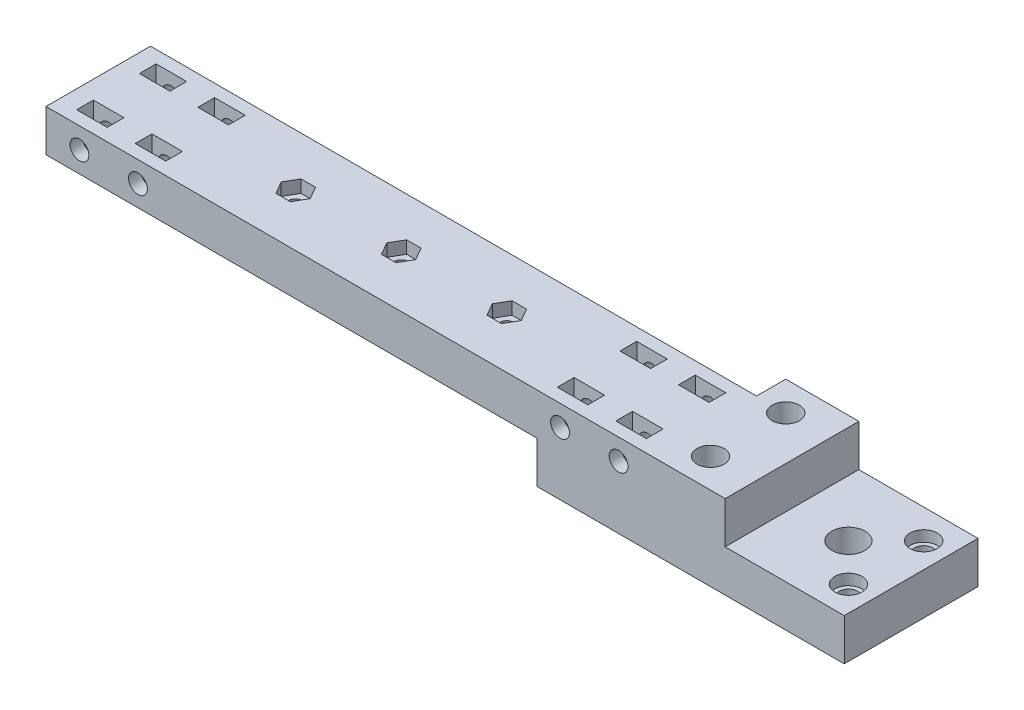
SolidWorks part; units mm, degrees
ref_plane "Front Plane" through (0, 0, 0) normal (0, 0, 1) x (1, 0, 0)
ref_plane "Top Plane" through (0, 0, 0) normal (0, 1, 0) x (1, 0, 0)
ref_plane "Right Plane" through (0, 0, 0) normal (1, 0, 0) x (0, 0, -1)
sketch "Sketch1" plane through (0, 0, 0) normal (0, 1, 0) x (1, 0, 0)
  line L7 (0, 0) -> (145, 0)
  line L8 (0, 0) -> (0, 25)
  line L9 (0, 25) -> (145, 25)
  line L10 (145, 0) -> (145, 25)
  dimension "D1" = 25
  dimension "D3" = 145
extrude "Boss-Extrude1" add sketch "Sketch1" along normal blind 10
sketch "Sketch2" plane through (0, 10, 0) normal (0, 1, 0) x (1, 0, 0)
  line L5 (145, 0) -> (162.5, 0)
  line L6 (145, 0) -> (145, 32)
  line L7 (145, 32) -> (162.5, 32)
  line L8 (162.5, 0) -> (162.5, 32)
  dimension "D1" = 17.5
  dimension "D2" = 32
extrude "Boss-Extrude2" add sketch "Sketch2" against normal blind 10
sketch "Sketch4" plane through (0, 0, 0) normal (0, -1, 0) x (1, 0, 0)
  line L0 (162.5, -32) -> (191, -32) construction
  line L1 (162.5, 0) -> (117.5, 0) construction
  line L2 (0, 0) -> (162.5, 0) construction
  line L4 (117.5, 0) -> (191, 0)
  line L5 (117.5, 0) -> (117.5, -32)
  line L6 (117.5, -32) -> (191, -32)
  line L7 (191, 0) -> (191, -32)
  dimension "D1" = 28.5
  dimension "D2" = 45
extrude "Boss-Extrude3" add sketch "Sketch4" along normal blind 10
sketch "Sketch5" plane through (0, -10, 0) normal (0, -1, 0) x (1, 0, 0)
  line L0 (191, -16) -> (117.5, -16) construction
  line L1 (191, -32) -> (191, 0) construction
  line L2 (117.5, 0) -> (117.5, -32) construction
  line L3 (117.5, -12.5) -> (191, -12.5) construction
  line L4 (117.5, 0) -> (117.5, -25) construction
  circle A0 centre (185, -7) radius 2.25
  circle A1 centre (152, -7) radius 2.25
  circle A2 centre (185, -25) radius 2.25
  circle A3 centre (152, -25) radius 2.25
  dimension "D1" = 4.5
  dimension "D2" = 6
  dimension "D3" = 9
  dimension "D5" = 33
  dimension "D4" = 2
extrude "Cut-Extrude1" cut sketch "Sketch5" against normal up to next
sketch "Sketch6" plane through (0, -10, 0) normal (0, -1, 0) x (1, 0, 0)
  line L0 (191, -16) -> (117.5, -16) construction
  line L1 (191, -32) -> (191, 0) construction
  line L2 (117.5, 0) -> (117.5, -32) construction
  circle A0 centre (152, -7) radius 4.2
  circle A1 centre (185, -7) radius 4.2
  circle A2 centre (185, -25) radius 4.2
  circle A3 centre (152, -25) radius 4.2
  dimension "D1" = 8.4
  dimension "D3" = 33
  dimension "D2" = 2
extrude "Cut-Extrude2" cut sketch "Sketch6" against normal blind 2.4
sketch "Sketch7" plane through (0, -7.6, 0) normal (0, -1, 0) x (1, 0, 0)
  line L0 (191, -16) -> (117.5, -16) construction
  line L1 (191, -32) -> (191, 0) construction
  line L2 (117.5, 0) -> (117.5, -32) construction
  circle A0 centre (152, -7) radius 3.25
  circle A1 centre (185, -7) radius 3.25
  circle A2 centre (185, -25) radius 3.25
  circle A3 centre (152, -25) radius 3.25
  dimension "D1" = 6.5
  dimension "D3" = 33
  dimension "D2" = 2
extrude "Cut-Extrude4" cut sketch "Sketch7" against normal up to next from offset 5 offset against normal yes
sketch "Sketch8" plane through (0, 0, -25) normal (0, 0, -1) x (-1, 0, 0)
  line L0 (-145, 5) -> (0, 5) construction
  line L1 (-145, 10) -> (-145, 0) construction
  line L2 (0, 10) -> (0, 0) construction
  line L3 (-72.5, 10) -> (-72.5, 0) construction
  line L4 (0, 10) -> (-145, 10) construction
  line L5 (0, 0) -> (-117.5, 0) construction
  circle A0 centre (-137, 5) radius 2.25
  circle A1 centre (-123, 5) radius 2.25
  circle A2 centre (-22, 5) radius 2.25
  circle A3 centre (-8, 5) radius 2.25
  dimension "D1" = 8
  dimension "D2" = 4.5
  dimension "D4" = 14
  dimension "D3" = 2
extrude "Cut-Extrude5" cut sketch "Sketch8" against normal through all
sketch "Sketch9" plane through (0, 10, 0) normal (0, 1, 0) x (1, 0, 0)
  line L0 (145, 25) -> (145, 0) construction
  line L1 (0, 0) -> (162.5, 0) construction
  line L2 (145, 12.5) -> (0, 12.5) construction
  line L3 (0, 0) -> (0, 25) construction
  line L4 (72.5, 25) -> (72.5, 0) construction
  line L5 (0, 25) -> (145, 25) construction
  line L6 (137, 0) -> (137, 25) construction
  line L7 (140.65, 22) -> (133.35, 22)
  line L8 (140.65, 7) -> (133.35, 7)
  line L9 (140.65, 7) -> (140.65, 3)
  line L10 (140.65, 3) -> (133.35, 3)
  line L11 (133.35, 7) -> (133.35, 3)
  line L12 (140.65, 7) -> (133.35, 3) construction
  line L13 (140.65, 3) -> (133.35, 7) construction
  line L14 (133.35, 18) -> (133.35, 22)
  line L15 (140.65, 18) -> (133.35, 18)
  line L16 (140.65, 18) -> (140.65, 22)
  line L17 (126.65, 7) -> (126.65, 3)
  line L18 (126.65, 7) -> (119.35, 7)
  line L19 (119.35, 7) -> (119.35, 3)
  line L20 (126.65, 3) -> (119.35, 3)
  line L21 (126.65, 22) -> (119.35, 22)
  line L22 (119.35, 18) -> (119.35, 22)
  line L23 (126.65, 18) -> (119.35, 18)
  line L24 (126.65, 18) -> (126.65, 22)
  line L25 (4.35, 18) -> (4.35, 22)
  line L26 (4.35, 18) -> (11.65, 18)
  line L27 (11.65, 18) -> (11.65, 22)
  line L28 (4.35, 22) -> (11.65, 22)
  line L29 (18.35, 18) -> (18.35, 22)
  line L30 (18.35, 18) -> (25.65, 18)
  line L31 (25.65, 18) -> (25.65, 22)
  line L32 (18.35, 22) -> (25.65, 22)
  line L33 (18.35, 7) -> (25.65, 7)
  line L34 (25.65, 7) -> (25.65, 3)
  line L35 (18.35, 3) -> (25.65, 3)
  line L36 (18.35, 7) -> (18.35, 3)
  line L37 (4.35, 3) -> (11.65, 3)
  line L38 (11.65, 7) -> (11.65, 3)
  line L39 (4.35, 7) -> (11.65, 7)
  line L40 (4.35, 7) -> (4.35, 3)
  point P15 (137, 5)
  dimension "D1" = 8
  dimension "D2" = 5
  dimension "D3" = 7.3
  dimension "D4" = 4
  dimension "D6" = 14
  dimension "D5" = 2
extrude "Cut-Extrude6" cut sketch "Sketch9" against normal up to surface (10 mm away) up to face at (58.75, 0, -12.5)
sketch "Sketch10" plane through (0, 0, 0) normal (0, 1, 0) x (1, 0, 0)
  line L0 (191, 16) -> (162.5, 16) construction
  line L1 (191, 32) -> (191, 0) construction
  line L2 (162.5, 0) -> (162.5, 32) construction
  circle A0 centre (176, 16) radius 4
  dimension "D1" = 15
  dimension "D2" = 8
extrude "Cut-Extrude7" cut sketch "Sketch10" against normal up to next
sketch "Sketch11" plane through (0, -10, 0) normal (0, -1, 0) x (1, 0, 0)
  line L0 (176, -16) -> (163.5, -16) construction
  line L1 (163.5, -21.5) -> (163.5, -10.5) construction
  line L2 (160.5, -21.5) -> (160.5, -10.5)
  line L3 (166.5, -21.5) -> (166.5, -10.5)
  circle A0 centre (176, -16) radius 7
  arc A1 (160.5, -21.5) -> (166.5, -21.5) centre (163.5, -21.5) ccw
  arc A2 (166.5, -10.5) -> (160.5, -10.5) centre (163.5, -10.5) ccw
  point P6 (163.5, -16)
  dimension "D1" = 14
  dimension "D3" = 6
  dimension "D2" = 12.5
  dimension "D4" = 11
extrude "Cut-Extrude8" cut sketch "Sketch11" against normal blind 2.5
sketch "Sketch12" plane through (0, 10, 0) normal (0, 1, 0) x (1, 0, 0)
  line L0 (22, 22) -> (22, 3) construction
  line L1 (25.65, 22) -> (18.35, 22) construction
  line L2 (18.35, 3) -> (25.65, 3) construction
  line L3 (123, 22) -> (123, 3) construction
  line L4 (126.65, 22) -> (119.35, 22) construction
  line L5 (119.35, 3) -> (126.65, 3) construction
  line L6 (22, 12.5) -> (123, 12.5) construction
  line L7 (0, 0) -> (162.5, 0) construction
  circle A0 centre (72.5, 12.5) radius 1.75
  circle A1 centre (97.75, 12.5) radius 1.75
  circle A2 centre (72.5, 12.5) radius 1.75
  circle A3 centre (47.25, 12.5) radius 1.75
  dimension "D1" = 3.5
  dimension "D4" = 25.25
  dimension "D5" = 25.25
  dimension "D6" = 12.5
  dimension "D2" = 2
  dimension "D3" = 2
extrude "Cut-Extrude9" cut sketch "Sketch12" against normal up to next contours A3 | A0 | A1
sketch "Sketch13" plane through (0, 10, 0) normal (0, 1, 0) x (1, 0, 0)
  line L0 (75.9641, 12.5) -> (74.2321, 15.5)
  line L1 (50.7141, 12.5) -> (48.9821, 15.5)
  line L2 (48.9821, 15.5) -> (45.5179, 15.5)
  line L3 (45.5179, 15.5) -> (43.7859, 12.5)
  line L4 (43.7859, 12.5) -> (45.5179, 9.5)
  line L5 (45.5179, 9.5) -> (48.9821, 9.5)
  line L6 (48.9821, 9.5) -> (50.7141, 12.5)
  line L7 (74.2321, 15.5) -> (70.7679, 15.5)
  line L8 (70.7679, 15.5) -> (69.0359, 12.5)
  line L9 (69.0359, 12.5) -> (70.7679, 9.5)
  line L10 (70.7679, 9.5) -> (74.2321, 9.5)
  line L11 (74.2321, 9.5) -> (75.9641, 12.5)
  line L12 (101.2141, 12.5) -> (99.4821, 15.5)
  line L13 (99.4821, 15.5) -> (96.0179, 15.5)
  line L14 (96.0179, 15.5) -> (94.2859, 12.5)
  line L15 (94.2859, 12.5) -> (96.0179, 9.5)
  line L16 (96.0179, 9.5) -> (99.4821, 9.5)
  line L17 (99.4821, 9.5) -> (101.2141, 12.5)
  circle A0 centre (47.25, 12.5) radius 3 construction
  dimension "D1" = 6
  dimension "D4" = 25.25
  dimension "D2" = 3
  dimension "D3" = 3
extrude "Cut-Extrude10" cut sketch "Sketch13" against normal blind 3
